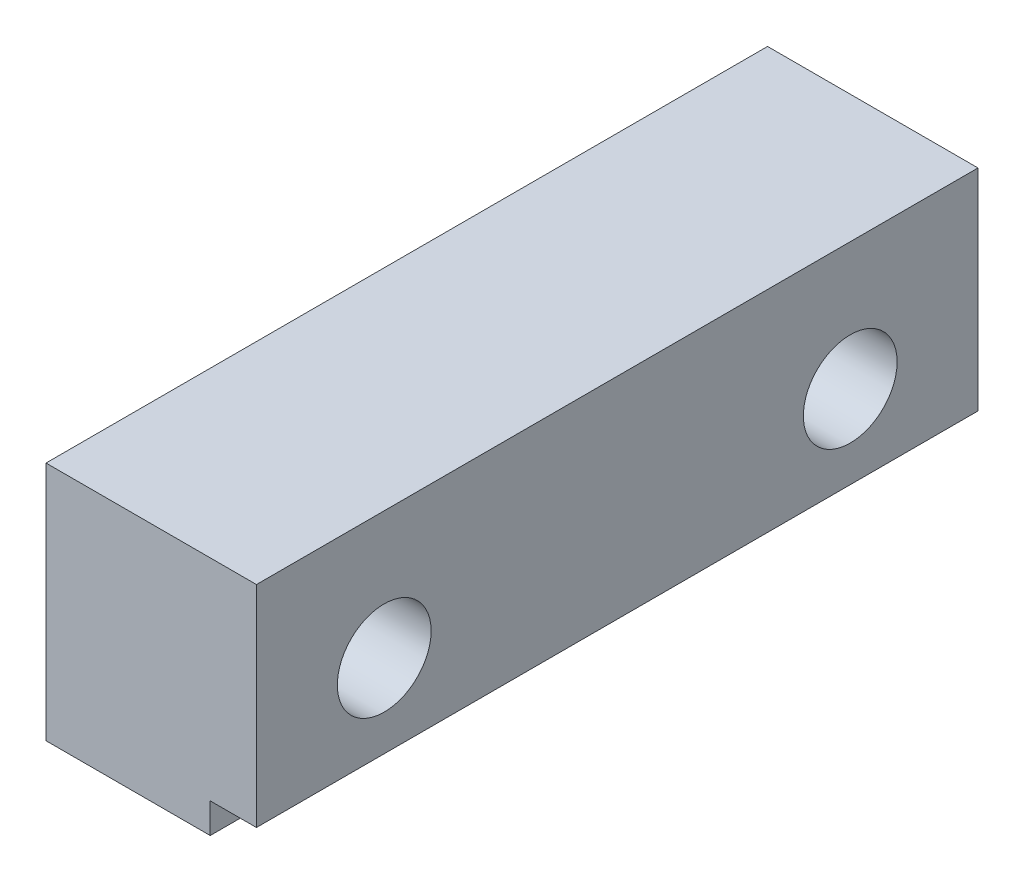
SolidWorks part; units mm, degrees
ref_plane "Front Plane" through (0, 0, 0) normal (0, 0, 1) x (1, 0, 0)
ref_plane "Top Plane" through (0, 0, 0) normal (0, 1, 0) x (1, 0, 0)
ref_plane "Right Plane" through (0, 0, 0) normal (1, 0, 0) x (0, 0, -1)
sketch "Sketch1" plane through (0, 0, 0) normal (0, 0, 1) x (1, 0, 0)
  line L1 (22.225, -25.4) -> (-22.225, -25.4)
  line L2 (22.225, -25.4) -> (22.225, 25.4)
  line L3 (22.225, 25.4) -> (-22.225, 25.4)
  line L4 (-22.225, -25.4) -> (-22.225, 25.4)
  line L5 (22.225, -25.4) -> (-22.225, 25.4) construction
  line L6 (22.225, 25.4) -> (-22.225, -25.4) construction
  point P0 (0, 0)
  dimension "D1" = 44.45
  dimension "D2" = 50.8
extrude "Boss-Extrude1" add sketch "Sketch1" along normal mid plane 152.4
sketch "Sketch2" plane through (22.225, 0, 0) normal (1, 0, 0) x (0, 0, -1)
  line L0 (-76.2, -25.4) -> (76.2, -25.4) construction
  circle A0 centre (-49.2125, -1.524) radius 6.731
  circle A1 centre (49.2125, -1.524) radius 6.731
  dimension "D4" = 13.462
  dimension "D1" = 98.425
  dimension "D2" = 49.2125
  dimension "D3" = 23.876
extrude "Cut-Extrude1" cut sketch "Sketch2" against normal up to next
sketch "Sketch3" plane through (22.225, 0, 0) normal (1, 0, 0) x (0, 0, -1)
  circle A0 centre (-49.2125, -1.524) radius 9.906
  circle A1 centre (49.2125, -1.524) radius 9.906
  dimension "D1" = 19.812
extrude "Cut-Extrude2" cut sketch "Sketch3" against normal blind 38.608
sketch "Sketch4" plane through (0, 0, 76.2) normal (0, 0, 1) x (1, 0, 0)
  line L7 (22.225, -25.4) -> (12.46, -25.4)
  line L8 (22.225, -25.4) -> (22.225, -19.05)
  line L9 (22.225, -19.05) -> (12.46, -19.05)
  line L10 (12.46, -25.4) -> (12.46, -19.05)
  dimension "D1" = 9.765
  dimension "D2" = 6.35
extrude "Cut-Extrude4" cut sketch "Sketch4" against normal through all
